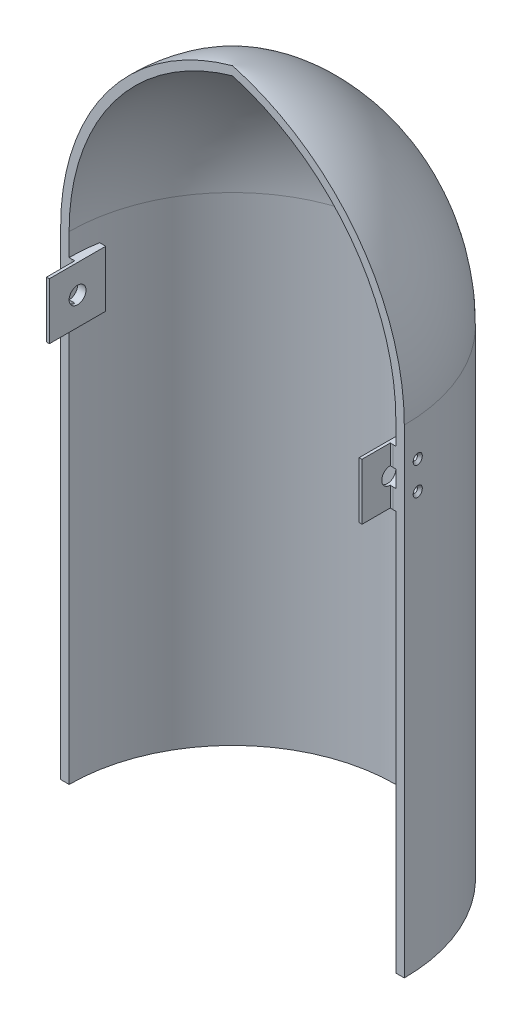
SolidWorks part; units mm, degrees
ref_plane "Front Plane" through (0, 0, 0) normal (0, 0, 1) x (1, 0, 0)
ref_plane "Top Plane" through (0, 0, 0) normal (0, 1, 0) x (1, 0, 0)
ref_plane "Right Plane" through (0, 0, 0) normal (1, 0, 0) x (0, 0, -1)
sketch "Sketch1" plane through (0, 0, 0) normal (0, 0, 1) x (1, 0, 0)
  line L4 (61, 170) -> (61, 0)
  line L5 (0, 246.8846) -> (0, 250)
  line L9 (58, 0) -> (61, 0)
  line L10 (0, 0) -> (0, 250) construction
  line L15 (58, 0) -> (58, 170) construction
  line L16 (61, 0) -> (61, 170) construction
  line L19 (58, 170) -> (58, 0)
  arc A0 (61, 170) -> (0, 250) centre (-21.959, 170) ccw
  arc A1 (58, 170) -> (0, 246.8846) centre (-21.959, 170) ccw
  arc A8 (58, 170) -> (-0.7941, 247.107) centre (-21.959, 170) ccw construction
  dimension "D2" = 170
  dimension "D3" = 80
  dimension "D5" = 61
  dimension "D4" = 3
revolve "Revolve1" add sketch "Sketch1" angle 180 about L10
sketch "Sketch2" plane through (0, 0, 0) normal (0, 0, 1) x (1, 0, 0)
  line L0 (58, 162) -> (55, 162)
  line L1 (-58, 170) -> (58, 170) construction
  line L2 (55, 162) -> (55, 142)
  line L3 (55, 142) -> (58, 142)
  line L4 (58, 170) -> (58, 0) construction
  line L5 (58, 142) -> (58, 162)
  line L6 (0, 251.6085) -> (0, 170) construction
  line L7 (-58, 142) -> (-58, 162)
  line L8 (-58, 162) -> (-55, 162)
  line L9 (-55, 162) -> (-55, 142)
  line L10 (-55, 142) -> (-58, 142)
  dimension "D1" = 3
  dimension "D2" = 20
  dimension "D3" = 8
extrude "Boss-Extrude1" add sketch "Sketch2" against normal blind 10
sketch "Sketch4" plane through (0, 0, 0) normal (0, 0, 1) x (1, 0, 0)
  line L0 (0, 170) -> (0, 142.6292) construction
  line L1 (-58, 170) -> (58, 170) construction
  line L2 (56.5, 142) -> (56.5, 162) construction
  line L3 (55, 142) -> (58, 142) construction
  line L4 (58, 162) -> (55, 162) construction
  line L5 (-56, 162) -> (-57, 162)
  line L6 (56, 142) -> (57, 142)
  line L7 (56, 142) -> (56, 162)
  line L8 (56, 162) -> (57, 162)
  line L9 (57, 142) -> (57, 162)
  line L10 (56, 142) -> (57, 162) construction
  line L11 (56, 162) -> (57, 142) construction
  line L12 (-56, 142) -> (-57, 142)
  line L13 (-56, 142) -> (-56, 162)
  line L14 (-57, 142) -> (-57, 162)
  point P11 (56.5, 152)
  dimension "D1" = 1
extrude "Cut-Extrude1" cut sketch "Sketch4" against normal blind 0.01
hole_wizard "CSK for M1.6 Countersunk Flat Head Screw2" positions "3DSketch2" profile "Sketch8" countersink size "M1.6" standard "ISO"
sketch3d "3DSketch2"
  line L0 (61, 0, 0) -> (61, 170, 0) construction
  line L1 (61, 170, 0) -> (61, 170, -17.1717) construction
  line L2 (61, 170, 0) -> (61, 170, -17.1717) construction
  line L4 (-61, 170, 0) -> (-61, 170, -37.0841) construction
  line L6 (-61, 0, 0) -> (-61, 170, 0) construction
  point P0 (60.7951, 157.0016, -4.9958)
  point P2 (60.7951, 147.0016, -4.9958)
  point P4 (-60.7951, 147.0016, -4.9958)
  point P6 (-60.7951, 157.0016, -4.9958)
  point P31 (0, 0, 0)
  point P32 (0, 0, 0)
  point P33 (0, 0, 0)
  dimension "D1" = 5
  dimension "D2" = 13
  dimension "D3" = 10
  dimension "D4" = 13
  dimension "D5" = 10
  dimension "D6" = 5
sketch "Sketch8" plane through (60.7951, 157.0016, -4.9958) normal (0, 1, 0) x (-0.0819, 0, -0.9966)
  line L0 (0, 0) -> (0, 5.5408)
  line L1 (0, 5.5408) -> (0.9, 5)
  line L2 (0.9, 5) -> (0.9, 0.9)
  line L3 (0.9, 0.9) -> (1.8, 0)
  line L5 (1.8, 0) -> (0, 0)
  line L6 (-0.9, 0.9) -> (-1.8, 0) construction
  line L10 (0, 5.5408) -> (-0.9, 5) construction
  line L11 (0, -6.35) -> (0, 107.95) construction
  dimension "Hole Dia." = 1.8
  dimension "Hole Depth" = 5
  dimension "Near C'Sink Dia." = 3.6
  dimension "Near C'Sink Angle" = 90
  dimension "Drill Angle" = 118
sketch "Sketch10" plane through (0, 0, -0.01) normal (0, 0, 1) x (1, 0, 0)
  line L0 (-56, 162) -> (-55, 162)
  line L1 (-55, 162) -> (-55, 142)
  line L2 (-55, 142) -> (-56, 142)
  line L3 (-56, 142) -> (-56, 162)
  line L4 (0, 0) -> (0, 170) construction
  line L5 (-58, 170) -> (58, 170) construction
  line L6 (55, 142) -> (56, 142)
  line L7 (56, 162) -> (55, 162)
  line L8 (56, 142) -> (56, 162)
  line L9 (55, 162) -> (55, 142)
  line L10 (-55, 142) -> (-55, 162) construction
  line L11 (-56, 142) -> (-56, 162) construction
  line L12 (56, 162) -> (55, 162) construction
  line L13 (55, 142) -> (56, 142) construction
  point P2 (0, 0)
extrude "Boss-Extrude2" add sketch "Sketch10" along normal blind 10.01
sketch "Sketch11" plane through (56, 0, 0) normal (1, 0, 0) x (0, 0, -1)
  line L0 (-10, 162) -> (0, 142) construction
  circle A0 centre (-5, 152) radius 3
  dimension "D1" = 6
sketch "Sketch12" plane through (-55, 0, 0) normal (1, 0, 0) x (0, 0, -1)
  line L0 (0, 162) -> (0, 142) construction
  line L1 (10, 162) -> (-10, 162) construction
  line L2 (10, 142) -> (-10, 142) construction
  circle A0 centre (0, 152) radius 3
  dimension "D1" = 6
extrude "Cut-Extrude4" cut sketch "Sketch12" against normal blind 3
sketch "Sketch13" plane through (55, 0, 0) normal (-1, 0, 0) x (0, 0, 1)
  line L0 (0, 162) -> (0, 142) construction
  line L1 (-10, 162) -> (10, 162) construction
  line L2 (-10, 142) -> (10, 142) construction
  circle A0 centre (0, 152) radius 3
  dimension "D1" = 6
extrude "Cut-Extrude5" cut sketch "Sketch13" against normal blind 3
